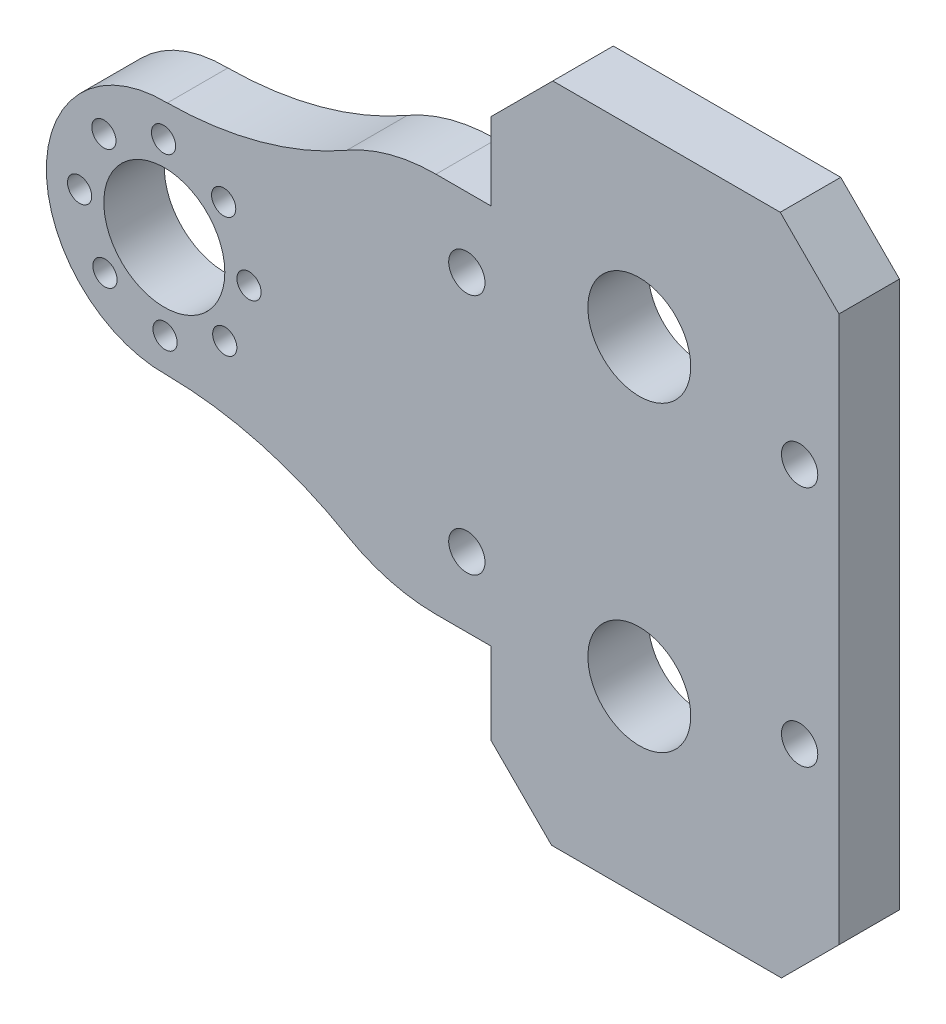
SolidWorks part; units mm, degrees
ref_plane "Front Plane" through (0, 0, 0) normal (0, 0, 1) x (1, 0, 0)
ref_plane "Top Plane" through (0, 0, 0) normal (0, 1, 0) x (1, 0, 0)
ref_plane "Right Plane" through (0, 0, 0) normal (1, 0, 0) x (0, 0, -1)
sketch "Sketch1" plane through (0, 0, 0) normal (0, 0, 1) x (1, 0, 0)
  line L30 (45.2509, -25.2077) -> (50.0009, -20.4577)
  line L31 (50.0009, -20.4577) -> (50.0009, 24.6887)
  line L32 (50.0009, 24.6887) -> (45.1474, 29.5423)
  line L33 (45.1474, 29.5423) -> (26.3545, 29.5423)
  line L34 (26.3545, 29.5423) -> (21.2509, 24.4387)
  line L35 (21.2509, 24.4387) -> (21.2509, 18.0423)
  line L36 (21.2509, 18.0423) -> (20.4081, 18.0423)
  line L37 (20.4081, 18.0423) -> (16.7009, 18.0423)
  line L38 (-5.4991, 12.0433) -> (-5.4991, 12.0391)
  line L39 (-5.4991, -7.4545) -> (-5.4991, -7.4587)
  line L40 (16.7009, -13.4577) -> (20.4081, -13.4577)
  line L41 (20.4081, -13.4577) -> (21.2509, -13.4577)
  line L42 (21.2509, -13.4577) -> (21.2509, -20.2077)
  line L43 (21.2509, -20.2077) -> (26.2509, -25.2077)
  line L44 (26.2509, -25.2077) -> (45.2509, -25.2077)
  arc A10 (16.7009, 18.0423) -> (9.3423, 16.0756) centre (16.7009, 3.2923) ccw
  arc A11 (-5.4991, 12.0433) -> (9.3423, 16.0756) centre (-5.7491, 42.2923) ccw
  arc A12 (-5.4991, 12.0391) -> (-5.4991, -7.4545) centre (-5.7491, 2.2923) ccw
  arc A13 (9.3423, -11.491) -> (-5.4991, -7.4587) centre (-5.7491, -37.7077) ccw
  arc A14 (9.3423, -11.491) -> (16.7009, -13.4577) centre (16.7009, 1.2923) ccw
  circle A25 centre (46.7509, -7.7077) radius 1.5
  circle A26 centre (46.7509, 12.2923) radius 1.5
  circle A27 centre (33.5009, 14.7923) radius 4.25
  circle A28 centre (33.5009, -10.2077) radius 4.25
  circle A29 centre (19.2509, 12.2923) radius 1.5
  circle A30 centre (19.2509, -7.7077) radius 1.5
  circle A31 centre (-5.7491, 2.2923) radius 1.5
  circle A32 centre (1.2509, 2.3547) radius 1
  circle A33 centre (-0.7554, -2.6131) radius 1
  circle A34 centre (-5.6866, -4.7077) radius 1
  circle A35 centre (-10.6545, -2.7014) radius 1
  circle A36 centre (-12.7491, 2.2298) radius 1
  circle A37 centre (-10.7428, 7.1977) radius 1
  circle A38 centre (-5.8115, 9.2923) radius 1
  circle A39 centre (-0.8437, 7.286) radius 1
extrude "Boss-Extrude2" add sketch "Sketch1" along normal blind 5
sketch "Sketch2" plane through (0, 0, 5) normal (0, 0, 1) x (1, 0, 0)
  circle A0 centre (-5.7491, 2.2923) radius 5
extrude "Cut-Extrude1" cut sketch "Sketch2" against normal blind 10
